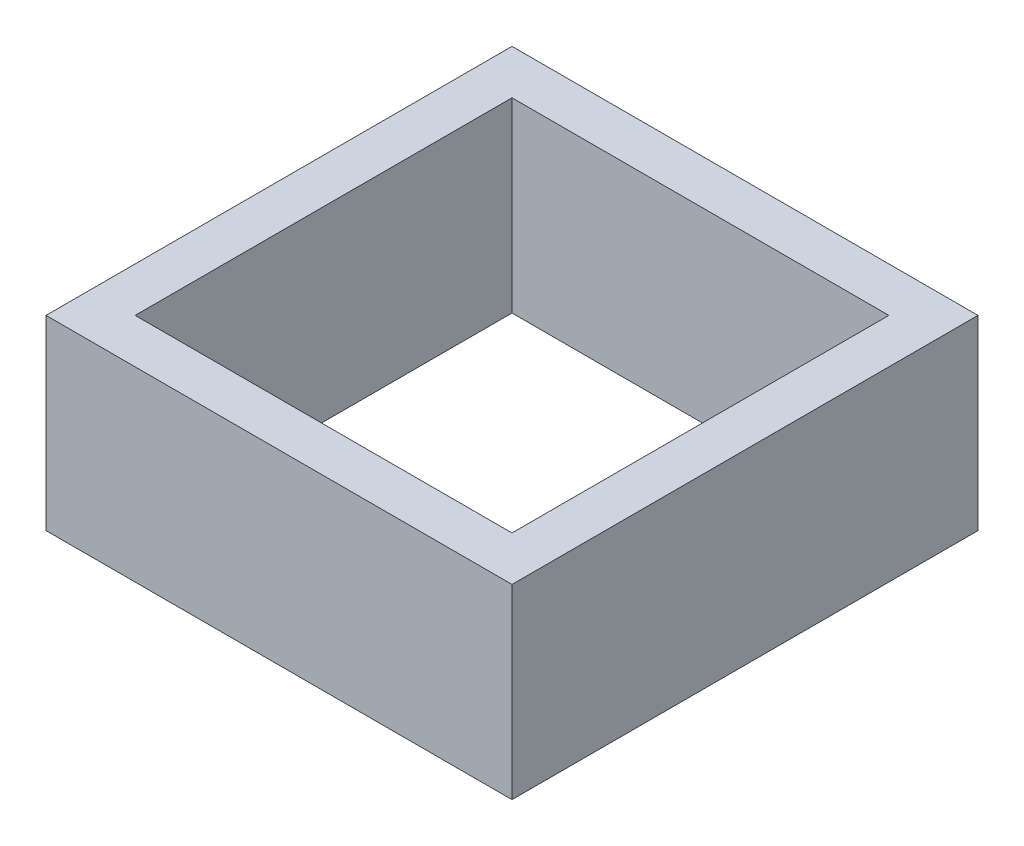
SolidWorks part; units mm, degrees
ref_plane "Plan de face" through (0, 0, 0) normal (0, 0, 1) x (1, 0, 0)
ref_plane "Plan de dessus" through (0, 0, 0) normal (0, 1, 0) x (1, 0, 0)
ref_plane "Plan de droite" through (0, 0, 0) normal (1, 0, 0) x (0, 0, -1)
sketch "Esquisse1" plane through (0, 0, 0) normal (0, 1, 0) x (1, 0, 0)
  line L1 (-115, 115) -> (115, 115)
  line L2 (-115, 115) -> (-115, -115)
  line L3 (-115, -115) -> (115, -115)
  line L4 (115, 115) -> (115, -115)
  line L5 (-115, 115) -> (115, -115) construction
  line L6 (-115, -115) -> (115, 115) construction
  line L7 (-93, 93) -> (93, 93)
  line L8 (-93, 93) -> (-93, -93)
  line L9 (-93, -93) -> (93, -93)
  line L10 (93, 93) -> (93, -93)
  line L11 (-93, 93) -> (93, -93) construction
  line L12 (-93, -93) -> (93, 93) construction
  point P4 (0, 0)
  point P5 (0, 0)
  point P11 (0, 0)
  dimension "D1" = 230
  dimension "D2" = 22
extrude "Boss.-Extru.1" add sketch "Esquisse1" along normal blind 92
